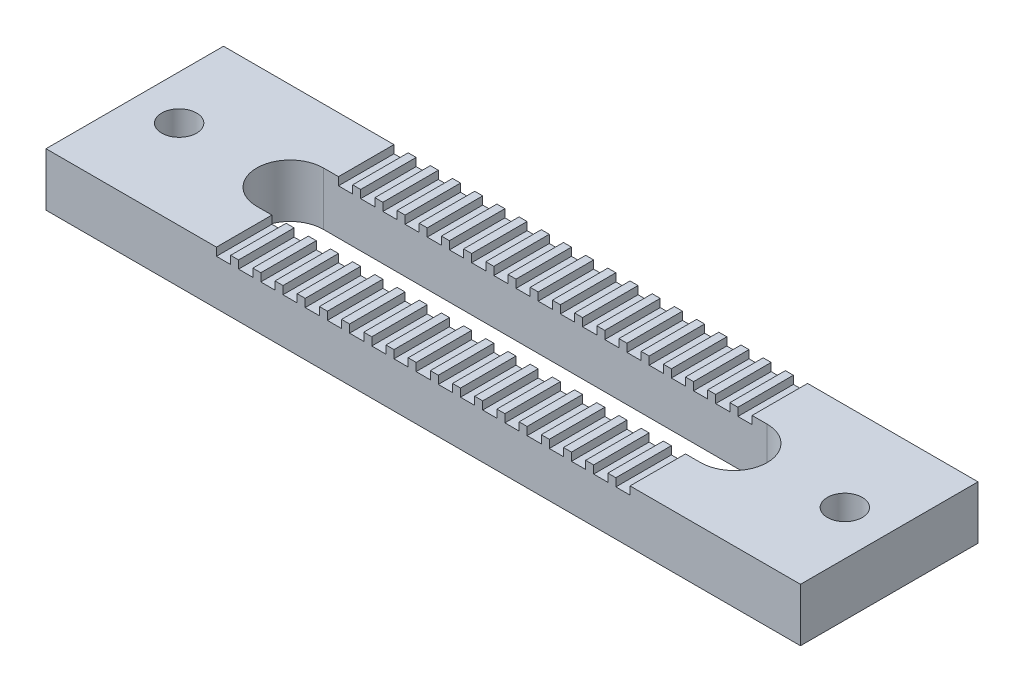
SolidWorks part; units mm, degrees
ref_plane "Front Plane" through (0, 0, 0) normal (0, 0, 1) x (1, 0, 0)
ref_plane "Top Plane" through (0, 0, 0) normal (0, 1, 0) x (1, 0, 0)
ref_plane "Right Plane" through (0, 0, 0) normal (1, 0, 0) x (0, 0, -1)
sketch "Sketch1" plane through (0, 0, 0) normal (0, 1, 0) x (1, 0, 0)
  line L0 (-31.75, 4.7625) -> (31.75, 4.7625)
  line L1 (-53.975, 12.7) -> (53.975, 12.7)
  line L2 (-53.975, 12.7) -> (-53.975, -12.7)
  line L3 (-53.975, -12.7) -> (53.975, -12.7)
  line L4 (53.975, 12.7) -> (53.975, -12.7)
  line L5 (31.75, -4.7625) -> (-31.75, -4.7625)
  arc A0 (-31.75, 4.7625) -> (-31.75, -4.7625) centre (-31.75, 0) ccw
  arc A1 (31.75, -4.7625) -> (31.75, 4.7625) centre (31.75, 0) ccw
  point P5 (0, 4.7625)
  point P12 (0, 12.7)
  point P13 (-53.975, 0)
  dimension "D1" = 9.525
  dimension "D2" = 107.95
  dimension "D3" = 63.5
  dimension "D4" = 25.4
extrude "Boss-Extrude1" add sketch "Sketch1" along normal blind 7.62
sketch "Sketch2" plane through (0, 7.62, 0) normal (0, 1, 0) x (1, 0, 0)
  line L0 (53.975, 12.7) -> (-53.975, 12.7) construction
  line L1 (-1.016, 12.7) -> (1.016, 12.7)
  line L2 (-1.016, 12.7) -> (-1.016, -12.7)
  line L3 (-1.016, -12.7) -> (1.016, -12.7)
  line L4 (1.016, 12.7) -> (1.016, -12.7)
  line L5 (-53.975, -12.7) -> (53.975, -12.7) construction
  point P11 (0, 12.7)
  dimension "D1" = 2.032
  dimension "D2" = 0
extrude "Cut-Extrude1" cut sketch "Sketch2" against normal blind 1.143
pattern_linear "LPattern1" count 10 spacing 3.175 along (1, 0, 0) of "Cut-Extrude1"
mirror "Mirror1" about plane through (0, 0, 0) normal (1, 0, 0) of "LPattern1"
sketch "Sketch3" plane through (0, 7.62, 0) normal (0, 1, 0) x (1, 0, 0)
  line L0 (-47.625, 0) -> (47.625, 0) construction
  circle A0 centre (-47.625, 0) radius 2.5
  circle A1 centre (47.625, 0) radius 2.5
  point P3 (0, 0)
  dimension "D1" = 5
  dimension "D2" = 95.25
extrude "Cut-Extrude2" cut sketch "Sketch3" against normal through all
